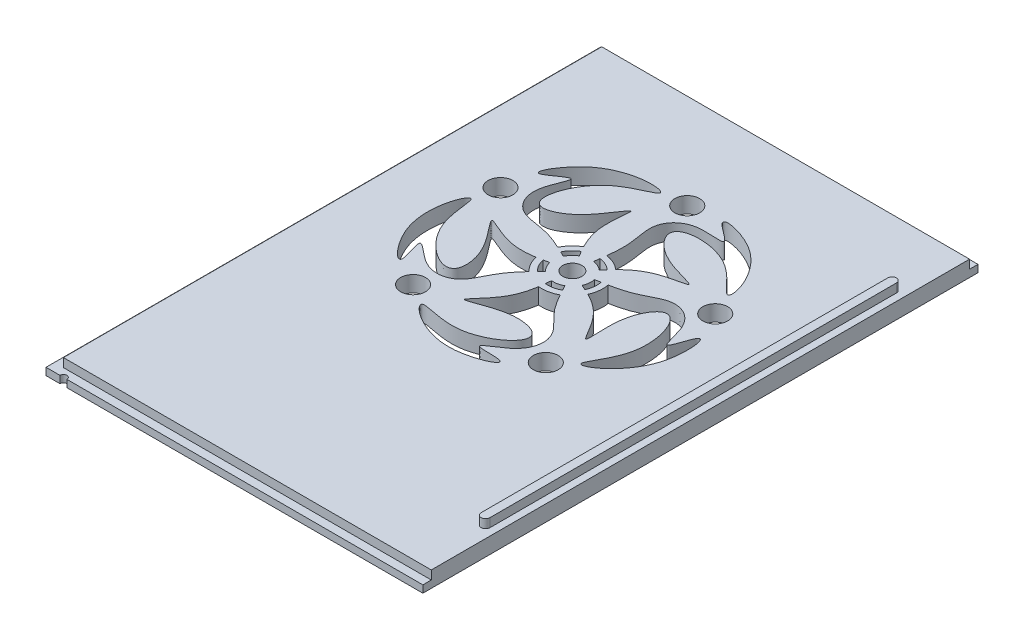
SolidWorks part; units mm, degrees
ref_plane "Front Plane" through (0, 0, 0) normal (0, 0, 1) x (1, 0, 0)
ref_plane "Top Plane" through (0, 0, 0) normal (0, 1, 0) x (1, 0, 0)
ref_plane "Right Plane" through (0, 0, 0) normal (1, 0, 0) x (0, 0, -1)
sketch "Sketch1" plane through (0, 0, 0) normal (0, 1, 0) x (1, 0, 0)
  line L1 (0, 0) -> (-64.9, 0)
  line L2 (0, 0) -> (0, 95.6)
  line L3 (0, 95.6) -> (-64.9, 95.6)
  line L4 (-64.9, 0) -> (-64.9, 95.6)
  dimension "D1" = 64.9
  dimension "D2" = 95.6
extrude "Boss-Extrude1" add sketch "Sketch1" along normal blind 1.25
sketch "Sketch2" plane through (0, 1.25, 0) normal (0, 1, 0) x (1, 0, 0)
  line L0 (0, 47.8) -> (-2, 47.8)
  line L1 (0, 0) -> (0, 95.6) construction
  line L2 (-2, 12.8) -> (-2, 82.8) construction
  line L3 (-2.75, 12.8) -> (-2.75, 82.8)
  line L4 (-1.25, 12.8) -> (-1.25, 82.8)
  arc A0 (-2.75, 12.8) -> (-1.25, 12.8) centre (-2, 12.8) ccw
  arc A1 (-1.25, 82.8) -> (-2.75, 82.8) centre (-2, 82.8) ccw
  point P6 (-2, 47.8)
  dimension "D2" = 0.75
  dimension "D1" = 2
  dimension "D3" = 70
extrude "Boss-Extrude2" add sketch "Sketch2" along normal blind 3 contours L4 A1 L3 A0
sketch "Sketch3" plane through (0, 1.25, 0) normal (0, 1, 0) x (1, 0, 0)
  line L6 (-36.2905, 60.017) -> (-35.4024, 59.5962)
  line L8 (-32.0319, 61.4375) -> (-31.9061, 62.4121)
  line L9 (-29.6123, 61.3609) -> (-30.2685, 60.6294)
  line L10 (-29.4628, 56.8741) -> (-28.5643, 56.4761)
  line L11 (-29.2391, 58.8009) -> (-28.2734, 58.9825)
  line L12 (-35.6444, 57.512) -> (-36.6053, 57.3058)
  line L13 (-34.6928, 55.8217) -> (-35.3675, 55.1071)
  line L14 (-30.8837, 55.3301) -> (-30.4126, 54.4677)
  line L15 (-32.7853, 54.9474) -> (-32.8862, 53.9699)
  line L17 (-34.0889, 61.0236) -> (-34.5819, 61.8737)
  arc A4 (-35.0992, 62.7658) -> (-37.2224, 60.4586) centre (-32.45, 58.1973) ccw
  arc A5 (-36.6053, 57.3058) -> (-35.3675, 55.1071) centre (-32.45, 58.1973) ccw
  arc A6 (-35.6444, 57.512) -> (-34.6928, 55.8217) centre (-32.45, 58.1973) ccw
  arc A7 (-37.6135, 57.0895) -> (-36.0754, 54.3572) centre (-32.45, 58.1973) ccw
  arc A8 (-32.9921, 52.9441) -> (-29.9182, 53.5627) centre (-32.45, 58.1973) ccw
  arc A9 (-27.6215, 56.0584) -> (-27.2599, 59.173) centre (-32.45, 58.1973) ccw
  arc A10 (-28.9237, 62.1286) -> (-31.7741, 63.4349) centre (-32.45, 58.1973) ccw
  arc A11 (-34.5819, 61.8737) -> (-36.2905, 60.017) centre (-32.45, 58.1973) ccw
  arc A12 (-34.0889, 61.0236) -> (-35.4024, 59.5962) centre (-32.45, 58.1973) ccw
  arc A13 (-29.6123, 61.3609) -> (-31.9061, 62.4121) centre (-32.45, 58.1973) ccw
  arc A14 (-30.2685, 60.6294) -> (-32.0319, 61.4375) centre (-32.45, 58.1973) ccw
  arc A15 (-28.5643, 56.4761) -> (-28.2734, 58.9825) centre (-32.45, 58.1973) ccw
  arc A16 (-29.4628, 56.8741) -> (-29.2391, 58.8009) centre (-32.45, 58.1973) ccw
  arc A17 (-32.8862, 53.9699) -> (-30.4126, 54.4677) centre (-32.45, 58.1973) ccw
  arc A18 (-32.7853, 54.9474) -> (-30.8837, 55.3301) centre (-32.45, 58.1973) ccw
  circle A19 centre (-32.45, 58.1973) radius 1.6451
  circle A24 centre (-32.2782, 77.8084) radius 2.1393
  circle A25 centre (-51.0482, 64.4208) radius 2.1393
  circle A26 centre (-44.1161, 42.4325) radius 2.1393
  circle A27 centre (-21.0619, 42.2306) radius 2.1393
  circle A28 centre (-13.7456, 64.0941) radius 2.1393
  spline S0 degree 3 poles (-37.2224, 60.4586) (-38.1228, 60.8823) (-41.5398, 62.3132) (-45.9098, 61.8847) (-48.6913, 66.9874) (-44.6488, 73.8061) (-52.2687, 67.2222) (-45.8199, 78.9342) (-32.1335, 77.9001) (-44.3484, 74.8039) (-47.6381, 63.3602) (-39.5012, 66.5051) (-35.1792, 75.3307) (-37.155, 67.6549) (-35.6394, 63.8295) (-35.0992, 62.7658) knots 0.085804 0.085804 0.085804 0.085804 0.112268 0.182407 0.240428 0.290229 0.334835 0.410844 0.52521 0.604529 0.709593 0.765862 0.843893 0.912604 0.943373 0.943373 0.943373 0.943373
  spline S1 degree 3 poles (-36.0754, 54.3572) (-36.7566, 53.6318) (-39.1734, 50.8242) (-40.1162, 46.5357) (-45.8287, 45.4671) (-51.0645, 51.419) (-47.1575, 42.1374) (-56.3035, 51.8898) (-51.0907, 64.5868) (-51.9207, 52.013) (-42.0536, 45.348) (-42.5301, 54.0585) (-49.5882, 60.8962) (-42.8986, 56.6451) (-38.7921, 56.9045) (-37.6135, 57.0895) knots 0.091656 0.091656 0.091656 0.091656 0.11812 0.188259 0.24628 0.296081 0.340687 0.416696 0.531062 0.610381 0.715445 0.771714 0.849745 0.918456 0.949225 0.949225 0.949225 0.949225
  spline S2 degree 3 poles (-29.9182, 53.5627) (-29.4388, 52.6907) (-27.5155, 49.5245) (-23.7282, 47.3026) (-24.4772, 41.5395) (-31.7557, 38.3992) (-21.7211, 39.2468) (-33.8224, 33.5622) (-44.2871, 42.4434) (-32.5852, 37.7685) (-23.1973, 45.0931) (-31.6287, 47.3316) (-40.3128, 42.7319) (-34.2026, 47.7804) (-33.1803, 51.7661) (-32.9921, 52.9441) knots 0.085804 0.085804 0.085804 0.085804 0.112268 0.182407 0.240428 0.290229 0.334835 0.410844 0.52521 0.604529 0.709593 0.765862 0.843893 0.912604 0.943373 0.943373 0.943373 0.943373
  spline S3 degree 3 poles (-27.2599, 59.173) (-26.2824, 59.3595) (-22.6769, 60.2103) (-19.3934, 63.1256) (-14.1438, 60.6324) (-13.4063, 52.7397) (-11.1116, 62.5451) (-9.4447, 49.2794) (-21.125, 42.0713) (-13.0629, 51.7559) (-17.1279, 62.9477) (-21.8623, 55.6207) (-20.1712, 45.9402) (-23.0845, 53.3114) (-26.5592, 55.5154) (-27.6215, 56.0584) knots 0.085804 0.085804 0.085804 0.085804 0.112268 0.182407 0.240428 0.290229 0.334835 0.410844 0.52521 0.604529 0.709593 0.765862 0.843893 0.912604 0.943373 0.943373 0.943373 0.943373
  spline S4 degree 3 poles (-31.7741, 63.4349) (-31.6494, 64.4222) (-31.3444, 68.1141) (-33.1024, 72.1378) (-29.109, 76.36) (-21.3747, 74.6224) (-29.9911, 79.8348) (-16.8596, 77.3208) (-13.6137, 63.9848) (-20.3329, 74.6451) (-32.2332, 74.2375) (-26.7277, 67.4706) (-16.9985, 66.0874) (-24.9092, 65.5946) (-28.079, 62.971) (-28.9237, 62.1286) knots 0.085804 0.085804 0.085804 0.085804 0.112268 0.182407 0.240428 0.290229 0.334835 0.410844 0.52521 0.604529 0.709593 0.765862 0.843893 0.912604 0.943373 0.943373 0.943373 0.943373
  dimension "D1" = 5
extrude "Cut-Extrude1" cut sketch "Sketch3" against normal through all
sketch "Sketch4" plane through (0, 1.25, 0) normal (0, 1, 0) x (1, 0, 0)
  line L0 (-64.9, 95.6) -> (-61.9, 95.6)
  line L1 (0, 95.6) -> (-64.9, 95.6) construction
  line L2 (-61.9, 95.6) -> (-61.9, 0)
  line L3 (-64.9, 0) -> (0, 0) construction
  line L4 (-61.9, 0) -> (-64.9, 0)
  circle A0 centre (-61.9, 95.6) radius 0.6
  circle A1 centre (-61.9, 0) radius 0.6
  dimension "D2" = 1.2
  dimension "D1" = 3
extrude "Cut-Extrude2" cut sketch "Sketch4" against normal through all contours A0 | A1
sketch "Sketch5" plane through (0, 1.25, 0) normal (0, 1, 0) x (1, 0, 0)
  line L0 (0, 94.15) -> (-63.35, 94.15)
  line L1 (0, 0) -> (0, 95.6) construction
  line L2 (-63.35, 94.15) -> (-63.35, 1.45)
  line L3 (-63.35, 1.45) -> (0, 1.45)
  line L4 (0, 1.45) -> (0, 94.15)
  line L5 (0, 95.6) -> (-61.3, 95.6) construction
  line L6 (-64.9, 95.6) -> (-64.9, 0) construction
  line L7 (-61.3, 0) -> (0, 0) construction
  line L9 (-63.5, 94.3) -> (-0.5, 94.3) construction
  line L10 (-0.5, 1.3) -> (-31.3, 1.3) construction
  line L11 (-63.5, 1.3) -> (-63.5, 94.3) construction
  line L12 (-31.9061, 62.4121) -> (-32.0319, 61.4375) construction
  line L13 (-30.2685, 60.6294) -> (-29.6123, 61.3609) construction
  line L14 (-29.4628, 56.8741) -> (-28.5643, 56.4761) construction
  line L15 (-28.2734, 58.9825) -> (-29.2391, 58.8009) construction
  line L16 (-32.7853, 54.9474) -> (-32.8862, 53.9699) construction
  line L17 (-30.4126, 54.4677) -> (-30.8837, 55.3301) construction
  line L18 (-34.0889, 61.0236) -> (-34.5819, 61.8737) construction
  line L19 (-36.2905, 60.017) -> (-35.4024, 59.5962) construction
  line L20 (-35.6444, 57.512) -> (-36.6053, 57.3058) construction
  line L21 (-35.3675, 55.1071) -> (-34.6928, 55.8217) construction
  line L22 (-31.9061, 62.4121) -> (-32.0319, 61.4375)
  line L23 (-30.2685, 60.6294) -> (-29.6123, 61.3609)
  line L24 (-29.4628, 56.8741) -> (-28.5643, 56.4761)
  line L25 (-28.2734, 58.9825) -> (-29.2391, 58.8009)
  line L26 (-32.7853, 54.9474) -> (-32.8862, 53.9699)
  line L27 (-30.4126, 54.4677) -> (-30.8837, 55.3301)
  line L28 (-34.0889, 61.0236) -> (-34.5819, 61.8737)
  line L29 (-36.2905, 60.017) -> (-35.4024, 59.5962)
  line L30 (-35.6444, 57.512) -> (-36.6053, 57.3058)
  line L31 (-35.3675, 55.1071) -> (-34.6928, 55.8217)
  circle A0 centre (-21.0619, 42.2306) radius 2.1393 construction
  circle A1 centre (-13.7456, 64.0941) radius 2.1393 construction
  circle A2 centre (-51.0482, 64.4208) radius 2.1393 construction
  circle A3 centre (-32.2782, 77.8084) radius 2.1393 construction
  arc A4 (-27.6215, 56.0584) -> (-27.2599, 59.173) centre (-32.45, 58.1973) ccw construction
  arc A5 (-35.0992, 62.7658) -> (-37.2224, 60.4586) centre (-32.45, 58.1973) ccw construction
  arc A6 (-28.9237, 62.1286) -> (-31.7741, 63.4349) centre (-32.45, 58.1973) ccw construction
  arc A7 (-30.2685, 60.6294) -> (-32.0319, 61.4375) centre (-32.45, 58.1973) ccw construction
  arc A8 (-29.6123, 61.3609) -> (-31.9061, 62.4121) centre (-32.45, 58.1973) ccw construction
  arc A9 (-29.4628, 56.8741) -> (-29.2391, 58.8009) centre (-32.45, 58.1973) ccw construction
  arc A10 (-28.5643, 56.4761) -> (-28.2734, 58.9825) centre (-32.45, 58.1973) ccw construction
  arc A11 (-32.7853, 54.9474) -> (-30.8837, 55.3301) centre (-32.45, 58.1973) ccw construction
  circle A12 centre (-32.45, 58.1973) radius 1.6451 construction
  arc A13 (-34.5819, 61.8737) -> (-36.2905, 60.017) centre (-32.45, 58.1973) ccw construction
  arc A14 (-34.0889, 61.0236) -> (-35.4024, 59.5962) centre (-32.45, 58.1973) ccw construction
  arc A15 (-35.6444, 57.512) -> (-34.6928, 55.8217) centre (-32.45, 58.1973) ccw construction
  arc A16 (-36.6053, 57.3058) -> (-35.3675, 55.1071) centre (-32.45, 58.1973) ccw construction
  arc A17 (-32.8862, 53.9699) -> (-30.4126, 54.4677) centre (-32.45, 58.1973) ccw construction
  arc A18 (-32.9921, 52.9441) -> (-29.9182, 53.5627) centre (-32.45, 58.1973) ccw construction
  circle A19 centre (-44.1161, 42.4325) radius 2.1393 construction
  arc A20 (-37.6135, 57.0895) -> (-36.0754, 54.3572) centre (-32.45, 58.1973) ccw construction
  circle A21 centre (-21.0619, 42.2306) radius 2.1393
  circle A22 centre (-13.7456, 64.0941) radius 2.1393
  circle A23 centre (-51.0482, 64.4208) radius 2.1393
  circle A24 centre (-32.2782, 77.8084) radius 2.1393
  arc A25 (-27.6215, 56.0584) -> (-27.2599, 59.173) centre (-32.45, 58.1973) ccw
  arc A26 (-35.0992, 62.7658) -> (-37.2224, 60.4586) centre (-32.45, 58.1973) ccw
  arc A27 (-28.9237, 62.1286) -> (-31.7741, 63.4349) centre (-32.45, 58.1973) ccw
  arc A28 (-30.2685, 60.6294) -> (-32.0319, 61.4375) centre (-32.45, 58.1973) ccw
  arc A29 (-29.6123, 61.3609) -> (-31.9061, 62.4121) centre (-32.45, 58.1973) ccw
  arc A30 (-29.4628, 56.8741) -> (-29.2391, 58.8009) centre (-32.45, 58.1973) ccw
  arc A31 (-28.5643, 56.4761) -> (-28.2734, 58.9825) centre (-32.45, 58.1973) ccw
  arc A32 (-32.7853, 54.9474) -> (-30.8837, 55.3301) centre (-32.45, 58.1973) ccw
  circle A33 centre (-32.45, 58.1973) radius 1.6451
  arc A34 (-34.5819, 61.8737) -> (-36.2905, 60.017) centre (-32.45, 58.1973) ccw
  arc A35 (-34.0889, 61.0236) -> (-35.4024, 59.5962) centre (-32.45, 58.1973) ccw
  arc A36 (-35.6444, 57.512) -> (-34.6928, 55.8217) centre (-32.45, 58.1973) ccw
  arc A37 (-36.6053, 57.3058) -> (-35.3675, 55.1071) centre (-32.45, 58.1973) ccw
  arc A38 (-32.8862, 53.9699) -> (-30.4126, 54.4677) centre (-32.45, 58.1973) ccw
  arc A39 (-32.9921, 52.9441) -> (-29.9182, 53.5627) centre (-32.45, 58.1973) ccw
  circle A40 centre (-44.1161, 42.4325) radius 2.1393
  arc A41 (-37.6135, 57.0895) -> (-36.0754, 54.3572) centre (-32.45, 58.1973) ccw
  spline S0 degree 3 poles (-1822.163, 960.2077) (107.1422, 33.8008) (-44.7097, 38.3051) (-35.1792, 75.3307) (-39.5012, 66.5051) (-47.6381, 63.3602) (-44.3484, 74.8039) (-32.1335, 77.9001) (-45.8199, 78.9342) (-52.2687, 67.2222) (-44.6488, 73.8061) (-48.6913, 66.9874) (-45.9098, 61.8847) (-22.7094, 64.16) (41.6847, -39.6649) (-1428.6091, 1497.0214) knots -0.592935 -0.592935 -0.592935 -0.592935 0.116573 0.185284 0.263314 0.319583 0.424648 0.503967 0.618333 0.694342 0.738948 0.788749 0.84677 0.916909 1.609653 1.609653 1.609653 1.609653 only from (-35.0992, 62.7658) to (-37.2224, 60.4586) construction
  spline S1 degree 3 poles (272.3668, 2039.1075) (-12.5154, -82.1039) (-55.1573, 63.7099) (-16.9985, 66.0874) (-26.7277, 67.4706) (-32.2332, 74.2375) (-20.3329, 74.6451) (-13.6137, 63.9848) (-16.8596, 77.3208) (-29.9911, 79.8348) (-21.3747, 74.6224) (-29.109, 76.36) (-33.1024, 72.1378) (-23.7692, 50.7761) (-102.6127, -42.5491) (904.4984, 1830.61) knots -0.592941 -0.592941 -0.592941 -0.592941 0.116573 0.185284 0.263314 0.319583 0.424648 0.503967 0.618333 0.694342 0.738948 0.788749 0.84677 0.916909 1.609649 1.609649 1.609649 1.609649 only from (-28.9237, 62.1286) to (-31.7741, 63.4349) construction
  spline S2 degree 3 poles (1945.7012, 380.4342) (-159.7243, -4.1171) (-34.2241, 81.4967) (-20.1712, 45.9402) (-21.8623, 55.6207) (-17.1279, 62.9477) (-13.0629, 51.7559) (-21.125, 42.0713) (-9.4447, 49.2794) (-11.1116, 62.5451) (-13.4063, 52.7397) (-14.1438, 60.6324) (-19.3934, 63.1256) (-36.8254, 47.648) (-149.947, 93.7937) (1942.7476, -285.1879) knots -0.592941 -0.592941 -0.592941 -0.592941 0.116573 0.185284 0.263314 0.319583 0.424648 0.503967 0.618333 0.694342 0.738948 0.788749 0.84677 0.916909 1.609649 1.609649 1.609649 1.609649 only from (-27.6215, 56.0584) to (-27.2599, 59.173) construction
  spline S3 degree 3 poles (885.2979, -1723.5596) (-131.0444, 159.9861) (-10.8391, 67.0845) (-40.3128, 42.7319) (-31.6287, 47.3316) (-23.1973, 45.0931) (-32.5852, 37.7685) (-44.2871, 42.4434) (-33.8224, 33.5622) (-21.7211, 39.2468) (-31.7557, 38.3992) (-24.4772, 41.5395) (-23.7282, 47.3026) (-43.835, 59.0987) (-34.9044, 180.9434) (251.3409, -1926.4392) knots -0.592941 -0.592941 -0.592941 -0.592941 0.116573 0.185284 0.263314 0.319583 0.424648 0.503967 0.618333 0.694342 0.738948 0.788748 0.84677 0.916909 1.609649 1.609649 1.609649 1.609649 only from (-32.9921, 52.9441) to (-29.9182, 53.5627) construction
  spline S4 degree 3 poles (-1443.3646, -1365.1844) (33.8888, 183.4184) (-17.3199, 40.3906) (-49.5882, 60.8962) (-42.5301, 54.0585) (-42.0536, 45.348) (-51.9207, 52.013) (-51.0907, 64.5868) (-56.3035, 51.8898) (-47.1575, 42.1374) (-51.0645, 51.419) (-45.8287, 45.4671) (-40.1162, 46.5357) (-35.1109, 69.3037) (83.5314, 98.4625) (-1832.2899, -825.0078) knots -0.587083 -0.587083 -0.587083 -0.587083 0.122425 0.191136 0.269166 0.325435 0.4305 0.509819 0.624185 0.700194 0.7448 0.7946 0.852622 0.922761 1.615505 1.615505 1.615505 1.615505 only from (-37.6135, 57.0895) to (-36.0754, 54.3572) construction
  spline S5 degree 3 poles (-35.0992, 62.7658) (-35.6394, 63.8295) (-37.155, 67.6549) (-35.1792, 75.3307) (-39.5012, 66.5051) (-47.6381, 63.3602) (-44.3484, 74.8039) (-32.1335, 77.9001) (-45.8199, 78.9342) (-52.2687, 67.2222) (-44.6488, 73.8061) (-48.6913, 66.9874) (-45.9098, 61.8847) (-41.5398, 62.3132) (-38.1228, 60.8823) (-37.2224, 60.4586) knots 0.085804 0.085804 0.085804 0.085804 0.116573 0.185284 0.263314 0.319583 0.424648 0.503967 0.618333 0.694342 0.738948 0.788749 0.84677 0.916909 0.943373 0.943373 0.943373 0.943373
  spline S6 degree 3 poles (-28.9237, 62.1286) (-28.079, 62.971) (-24.9092, 65.5946) (-16.9985, 66.0874) (-26.7277, 67.4706) (-32.2332, 74.2375) (-20.3329, 74.6451) (-13.6137, 63.9848) (-16.8596, 77.3208) (-29.9911, 79.8348) (-21.3747, 74.6224) (-29.109, 76.36) (-33.1024, 72.1378) (-31.3444, 68.1141) (-31.6494, 64.4222) (-31.7741, 63.4349) knots 0.085804 0.085804 0.085804 0.085804 0.116573 0.185284 0.263314 0.319583 0.424648 0.503967 0.618333 0.694342 0.738948 0.788749 0.84677 0.916909 0.943373 0.943373 0.943373 0.943373
  spline S7 degree 3 poles (-27.6215, 56.0584) (-26.5592, 55.5154) (-23.0845, 53.3114) (-20.1712, 45.9402) (-21.8623, 55.6207) (-17.1279, 62.9477) (-13.0629, 51.7559) (-21.125, 42.0713) (-9.4447, 49.2794) (-11.1116, 62.5451) (-13.4063, 52.7397) (-14.1438, 60.6324) (-19.3934, 63.1256) (-22.6769, 60.2103) (-26.2824, 59.3595) (-27.2599, 59.173) knots 0.085804 0.085804 0.085804 0.085804 0.116573 0.185284 0.263314 0.319583 0.424648 0.503967 0.618333 0.694342 0.738948 0.788749 0.84677 0.916909 0.943373 0.943373 0.943373 0.943373
  spline S8 degree 3 poles (-32.9921, 52.9441) (-33.1803, 51.7661) (-34.2026, 47.7804) (-40.3128, 42.7319) (-31.6287, 47.3316) (-23.1973, 45.0931) (-32.5852, 37.7685) (-44.2871, 42.4434) (-33.8224, 33.5622) (-21.7211, 39.2468) (-31.7557, 38.3992) (-24.4772, 41.5395) (-23.7282, 47.3026) (-27.5155, 49.5245) (-29.4388, 52.6907) (-29.9182, 53.5627) knots 0.085804 0.085804 0.085804 0.085804 0.116573 0.185284 0.263314 0.319583 0.424648 0.503967 0.618333 0.694342 0.738948 0.788748 0.84677 0.916909 0.943373 0.943373 0.943373 0.943373
  spline S9 degree 3 poles (-37.6135, 57.0895) (-38.7921, 56.9045) (-42.8986, 56.6451) (-49.5882, 60.8962) (-42.5301, 54.0585) (-42.0536, 45.348) (-51.9207, 52.013) (-51.0907, 64.5868) (-56.3035, 51.8898) (-47.1575, 42.1374) (-51.0645, 51.419) (-45.8287, 45.4671) (-40.1162, 46.5357) (-39.1734, 50.8242) (-36.7566, 53.6318) (-36.0754, 54.3572) knots 0.091656 0.091656 0.091656 0.091656 0.122425 0.191136 0.269166 0.325435 0.4305 0.509819 0.624185 0.700194 0.7448 0.7946 0.852622 0.922761 0.949225 0.949225 0.949225 0.949225
  dimension "D1" = 0.15
  dimension "D2" = 0.15
  dimension "D3" = 0.15
extrude "Boss-Extrude3" add sketch "Sketch5" along normal blind 1.5
